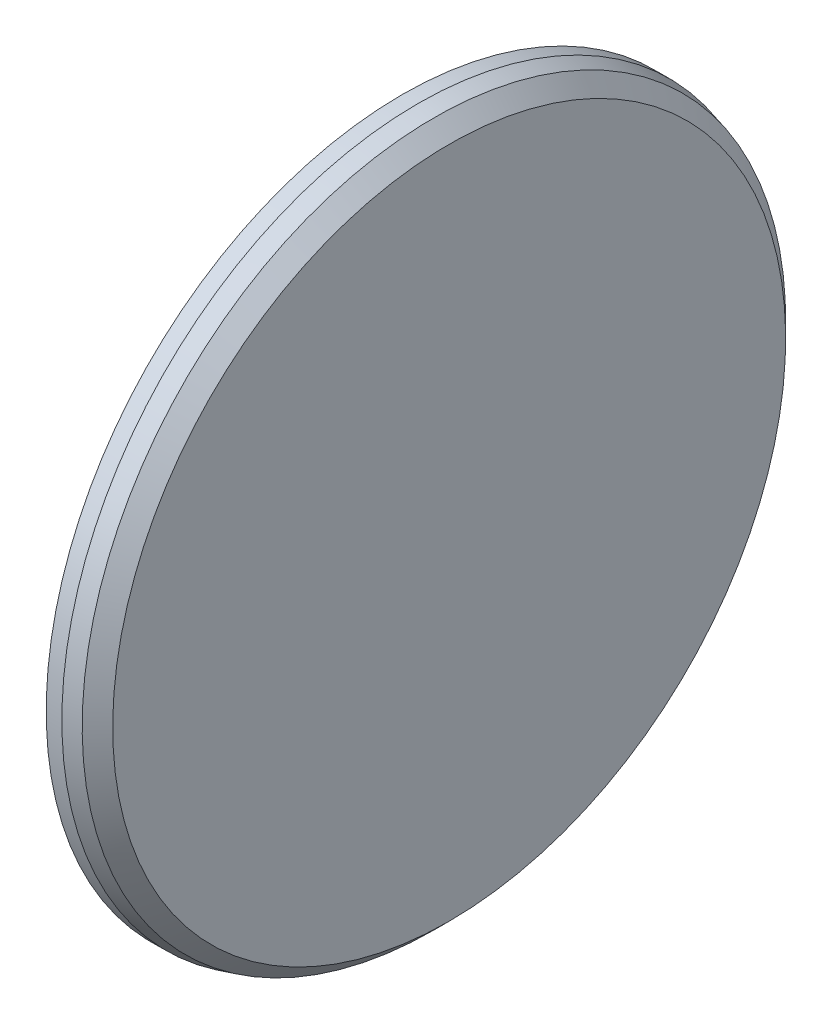
SolidWorks part; units mm, degrees
material "1060 Alloy"
ref_plane "Front Plane" through (0, 0, 0) normal (0, 0, 1) x (1, 0, 0)
ref_plane "Top Plane" through (0, 0, 0) normal (0, 1, 0) x (1, 0, 0)
ref_plane "Right Plane" through (0, 0, 0) normal (1, 0, 0) x (0, 0, -1)
sketch "Sketch1" plane through (0, 0, 0) normal (0, 0, 1) x (1, 0, 0)
  line L0 (-40, 0) -> (40, 0) construction
  line L1 (0, 0) -> (0, 74.4889) construction
  line L2 (0, 0) -> (0, -33.0272) construction
  line L3 (-40, 0) -> (40, 0)
  line L9 (-20, 455) -> (-20, 100)
  line L10 (-40, 0) -> (-40, 100)
  line L11 (-40, 100) -> (-20, 100)
  line L12 (-20, 100) -> (10, 100)
  line L13 (10, 100) -> (10, 410)
  line L14 (10, 410) -> (-20, 410)
  line L15 (-20, 410) -> (-20, 100)
  line L16 (-20, 455) -> (0, 455)
  line L17 (0, 455) -> (20.4904, 449.5096)
  line L18 (20.4904, 449.5096) -> (40, 430)
  line L19 (40, 0) -> (40, 430)
  point P3 (0, 0)
  dimension "D1" = 80
  dimension "D5" = 430
  dimension "D6" = 60
  dimension "D7" = 15
  dimension "D8" = 20
  dimension "D9" = 45
  dimension "D10" = 455
  dimension "D4" = 100
  dimension "D2" = 45
  dimension "D3" = 30
revolve "Revolve1" add sketch "Sketch1" angle 360 about L0
sketch "Sketch2" plane through (10, 0, 0) normal (-1, 0, 0) x (0, 0, 1)
  line L0 (0, 0) -> (0, 482.8234) construction
  line L1 (20, 105.8301) -> (20, 398.8734)
  line L2 (202.7387, 274.3565) -> (51.7098, 94.3672)
  circle A0 centre (0, 0) radius 100 construction
  circle A1 centre (0, 0) radius 410 construction
  arc A2 (40.0449, 91.6319) -> (27.2727, 96.2091) centre (0, 0) ccw
  arc A4 (20, 105.8301) -> (27.2727, 96.2091) centre (30, 105.8301) ccw
  arc A5 (51.7098, 94.3672) -> (40.0449, 91.6319) centre (44.0494, 100.7951) cw
  arc A6 (183.652, 366.5678) -> (30.75, 408.8452) centre (0, 0) ccw
  arc A7 (20, 398.8734) -> (30.75, 408.8452) centre (30, 398.8734) cw
  arc A8 (183.652, 366.5678) -> (202.7387, 274.3565) centre (156.7761, 312.9237) cw
  point P13 (20, 97.9796)
  point P16 (46.7168, 88.4168)
  point P19 (20, 409.5119)
  point P22 (247.0733, 327.1923)
  dimension "D3" = 10
  dimension "D4" = 10
  dimension "D5" = 10
  dimension "D6" = 60
  dimension "D1" = 20
  dimension "D2" = 40
extrude "Cut-Extrude3" cut sketch "Sketch2" against normal blind 10 contours A6 A7 L1 A4 A2 A5 L2 A8
pattern_circular "CirPattern1" count 9 over 360 about axis through (0, 0, 0) along (1, 0, 0) of "Cut-Extrude3"
equation "\"A\"= 60"
equation "\"B\"= 910"
equation "\"D1@Sketch1\"=\"A\"+20"
equation "\"D5@Sketch1\"=(\"B\"-50)/2"
equation "\"D6@Sketch1\"=\"A\""
equation "\"D10@Sketch1\"=\"B\"/2"
